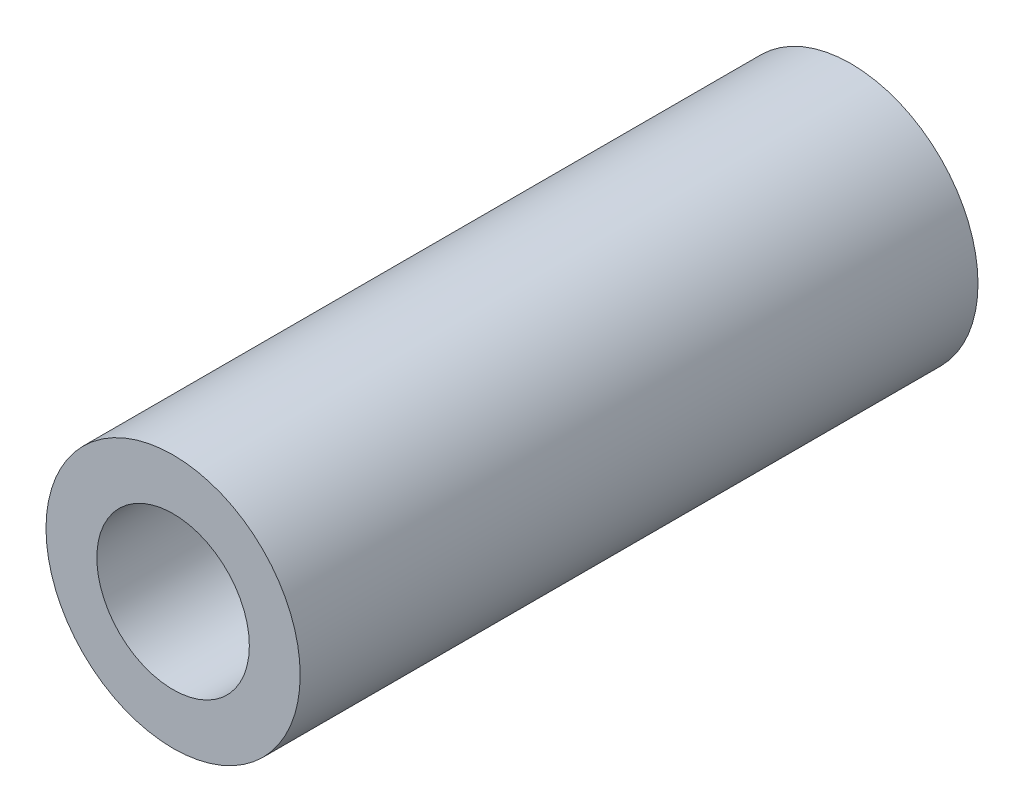
SolidWorks part; units mm, degrees
ref_plane "前视基准面" through (0, 0, 0) normal (0, 0, 1) x (1, 0, 0)
ref_plane "上视基准面" through (0, 0, 0) normal (0, 1, 0) x (1, 0, 0)
ref_plane "右视基准面" through (0, 0, 0) normal (1, 0, 0) x (0, 0, -1)
sketch "草图1" plane through (0, 0, 0) normal (0, 0, 1) x (1, 0, 0)
  circle A0 centre (0, 0) radius 4.5
  circle A1 centre (0, 0) radius 7.5
extrude "凸台-拉伸1" add sketch "草图1" along normal mid plane 40
